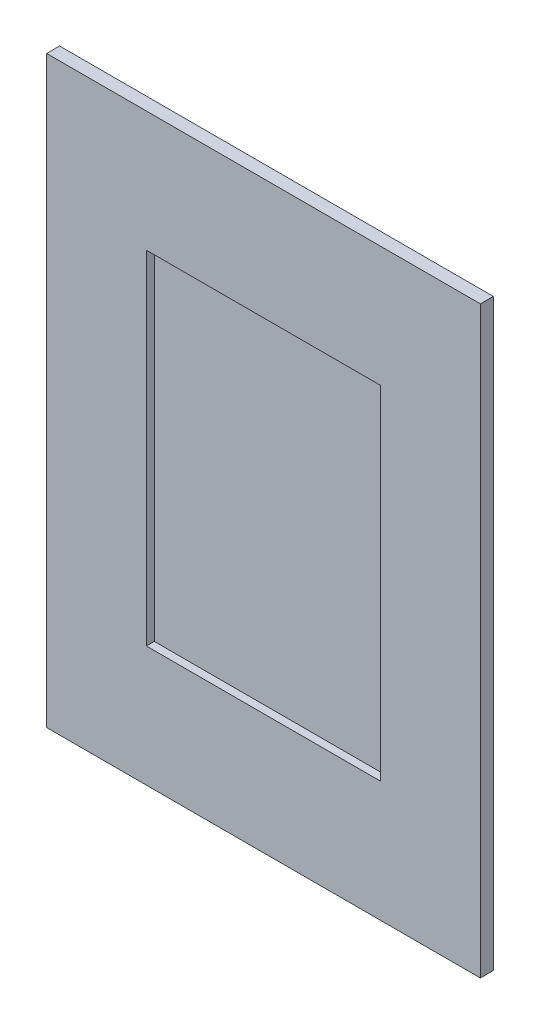
SolidWorks part; units mm, degrees
ref_plane "Front Plane" through (0, 0, 0) normal (0, 0, 1) x (1, 0, 0)
ref_plane "Top Plane" through (0, 0, 0) normal (0, 1, 0) x (1, 0, 0)
ref_plane "Right Plane" through (0, 0, 0) normal (1, 0, 0) x (0, 0, -1)
sketch "Sketch1" plane through (0, 0, 0) normal (0, 0, 1) x (1, 0, 0)
  line L1 (-32.9174, 24.8624) -> (19.0826, 24.8624)
  line L2 (-32.9174, 24.8624) -> (-32.9174, -45.1376)
  line L3 (-32.9174, -45.1376) -> (19.0826, -45.1376)
  line L4 (19.0826, 24.8624) -> (19.0826, -45.1376)
  dimension "D1" = 52
  dimension "D2" = 70
extrude "Boss-Extrude1" add sketch "Sketch1" along normal blind 1.55
sketch "Sketch2" plane through (0, 0, 1.55) normal (0, 0, 1) x (1, 0, 0)
  line L0 (19.0826, 24.8624) -> (-32.9174, 24.8624) construction
  line L1 (-20.9674, 10.4124) -> (7.1326, 10.4124)
  line L2 (-20.9674, 10.4124) -> (-20.9674, -30.6876)
  line L3 (-20.9674, -30.6876) -> (7.1326, -30.6876)
  line L4 (7.1326, 10.4124) -> (7.1326, -30.6876)
  line L5 (19.0826, -45.1376) -> (19.0826, 24.8624) construction
  dimension "D1" = 28.1
  dimension "D2" = 41.1
  dimension "D3" = 14.45
  dimension "D4" = 11.95
extrude "Cut-Extrude1" cut sketch "Sketch2" against normal blind 0.95
